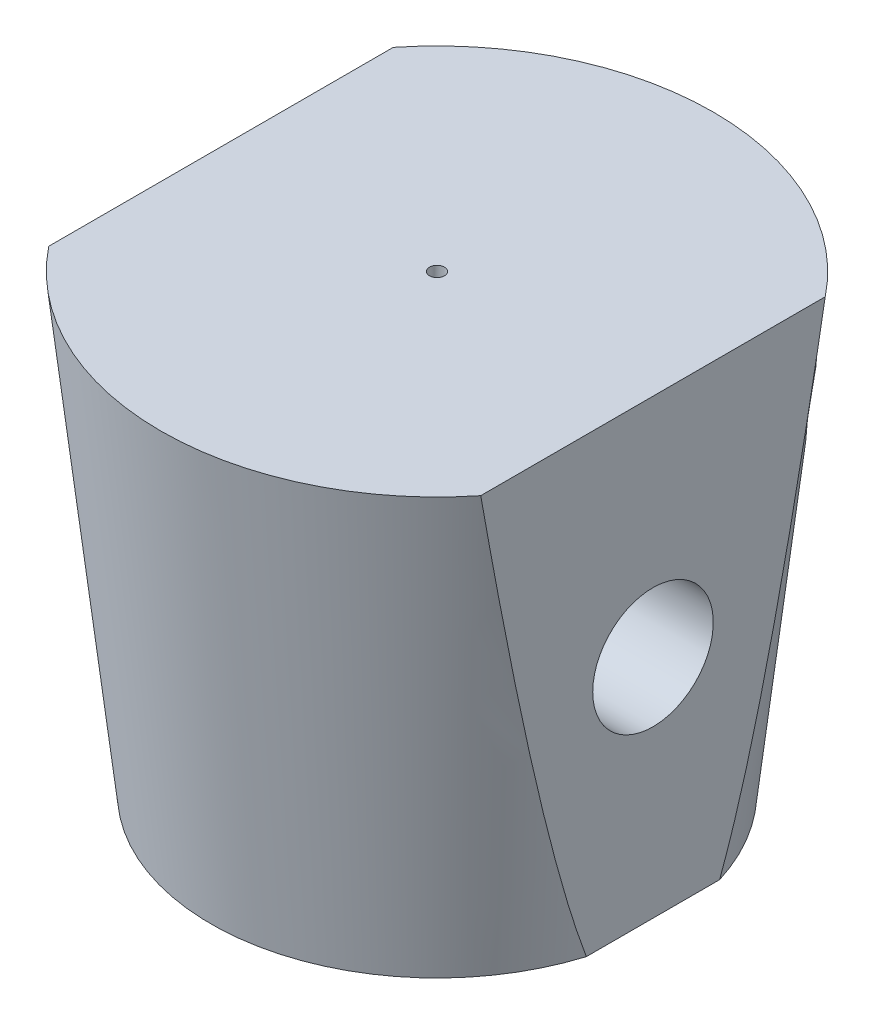
SolidWorks part; units mm, degrees
material "Epoxid, Ungefüllt"
ref_plane "Ebene vorne" through (0, 0, 0) normal (0, 0, 1) x (1, 0, 0)
ref_plane "Ebene oben" through (0, 0, 0) normal (0, 1, 0) x (1, 0, 0)
ref_plane "Ebene rechts" through (0, 0, 0) normal (1, 0, 0) x (0, 0, -1)
sketch "Skizze1" plane through (0, 0, 0) normal (0, 0, 1) x (1, 0, 0)
  line L0 (0, 0) -> (0, 55002.3159) construction
  line L1 (0, 0) -> (-22.5, 0)
  line L2 (-22.5, 0) -> (-27.5, 45)
  line L3 (-27.5, 45) -> (0, 45)
  line L4 (0, 45) -> (0, 0)
  dimension "D1" = 45
  dimension "D2" = 45
  dimension "D3" = 55
revolve "Rotation1" add sketch "Skizze1" angle 360 about L0
sketch "Skizze2" plane through (0, 45, 0) normal (0, 1, 0) x (1, 0, 0)
  circle A0 centre (0, 0) radius 0.75
  dimension "D1" = 1.5
extrude "Schnitt-Linear austragen1" cut sketch "Skizze2" against normal through all
sketch "Skizze3" plane through (0, 0, 0) normal (0, -1, 0) x (1, 0, 0)
  circle A0 centre (0, 0) radius 3.5
  dimension "D1" = 7
extrude "Schnitt-Linear austragen2" cut sketch "Skizze3" against normal blind 25
sketch "Skizze4" plane through (0, 0, 0) normal (1, 0, 0) x (0, 0, -1)
  line L0 (0, 0) -> (0, 45) construction
  line L1 (27.5, 45) -> (-27.5, 45) construction
  circle A0 centre (0, 22.5) radius 6
  dimension "D1" = 12
extrude "Schnitt-Linear austragen3" cut sketch "Skizze4" against normal blind 5 and the other way through all
sketch "Skizze5" plane through (0, 45, 0) normal (0, 1, 0) x (1, 0, 0)
  line L1 (-21.5, 30) -> (21.5, 30) construction
  line L2 (-21.5, 30) -> (-21.5, -30) construction
  line L3 (-21.5, -30) -> (21.5, -30) construction
  line L4 (21.5, 30) -> (21.5, -30) construction
  line L5 (-21.5, 30) -> (21.5, -30) construction
  line L6 (-21.5, -30) -> (21.5, 30) construction
  line L7 (-21.5, 30) -> (-31.5, 30)
  line L8 (-21.5, 30) -> (-21.5, -30)
  line L9 (-21.5, -30) -> (-31.5, -30)
  line L10 (-31.5, 30) -> (-31.5, -30)
  line L11 (-21.5, 30) -> (-31.5, -30) construction
  line L12 (-21.5, -30) -> (-31.5, 30) construction
  line L13 (21.5, 30) -> (31.5, 30)
  line L14 (21.5, 30) -> (21.5, -30)
  line L15 (21.5, -30) -> (31.5, -30)
  line L16 (31.5, 30) -> (31.5, -30)
  line L17 (21.5, 30) -> (31.5, -30) construction
  line L18 (21.5, -30) -> (31.5, 30) construction
  point P0 (0, 0)
  point P8 (-26.5, 0)
  point P11 (26.5, 0)
  dimension "D1" = 43
  dimension "D2" = 10
  dimension "D3" = 10
  dimension "D4" = 60
extrude "Schnitt-Linear austragen4" cut sketch "Skizze5" against normal through all
